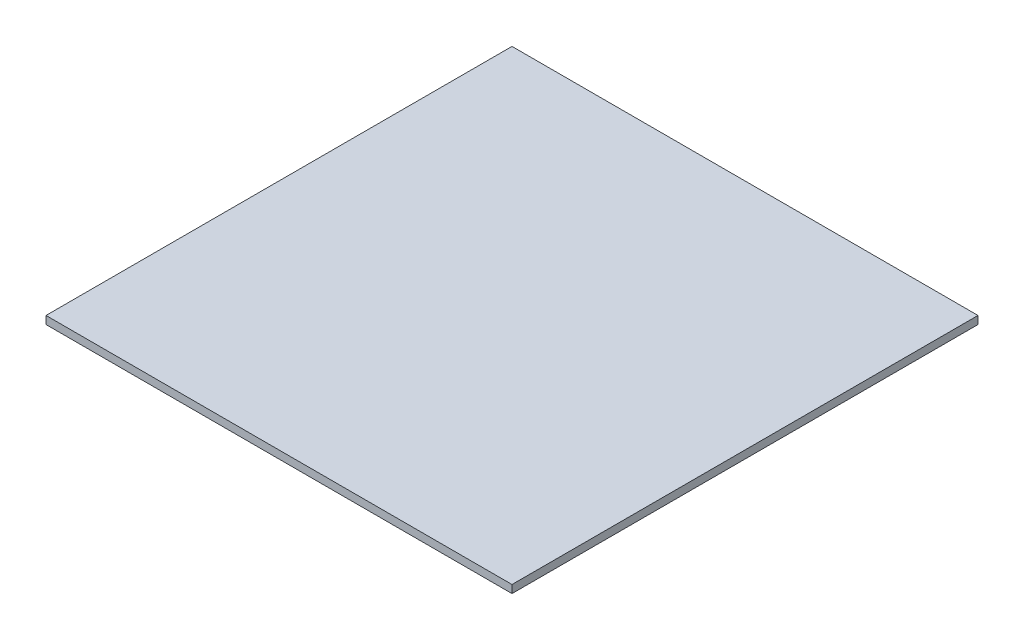
SolidWorks part; units mm, degrees
ref_plane "Alzado" through (0, 0, 0) normal (0, 0, 1) x (1, 0, 0)
ref_plane "Planta" through (0, 0, 0) normal (0, 1, 0) x (1, 0, 0)
ref_plane "Vista lateral" through (0, 0, 0) normal (1, 0, 0) x (0, 0, -1)
sketch "Croquis2" plane through (0, 0, 0) normal (0, 1, 0) x (1, 0, 0)
  line L1 (-750, -750) -> (750, -750)
  line L2 (-750, -750) -> (-750, 750)
  line L3 (-750, 750) -> (750, 750)
  line L4 (750, -750) -> (750, 750)
  line L5 (-750, -750) -> (750, 750) construction
  line L6 (-750, 750) -> (750, -750) construction
  point P0 (0, 0)
  dimension "D1" = 1500
  dimension "D2" = 1500
extrude "Saliente-Extruir1" add sketch "Croquis2" along normal blind 25.4
